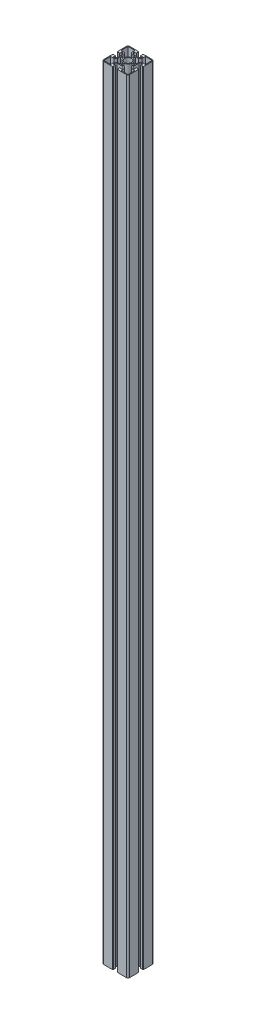
SolidWorks part; units mm, degrees
ref_plane "前视基准面" through (0, 0, 0) normal (0, 0, 1) x (1, 0, 0)
ref_plane "上视基准面" through (0, 0, 0) normal (0, 1, 0) x (1, 0, 0)
ref_plane "右视基准面" through (0, 0, 0) normal (1, 0, 0) x (0, 0, -1)
sketch "草图1" plane through (0, 0, 0) normal (0, 1, 0) x (1, 0, 0)
  line L0 (0, 32.6515) -> (0, -47.5) construction
  line L2 (-54.5455, 0) -> (57.7273, 0) construction
  line L82 (-16, 1) -> (-9.9499, 1)
  line L83 (-30, 6) -> (-28.5, 6)
  line L88 (-16, 1) -> (-16, 7.8284)
  line L89 (-16, 7.8284) -> (-20.1716, 12)
  line L90 (-20.1716, 12) -> (-28, 12)
  line L91 (-28, 12) -> (-28, 28)
  line L92 (-28, 28) -> (-12, 28)
  line L93 (-12, 28) -> (-12, 20.1716)
  line L94 (-12, 20.1716) -> (-7.8284, 16)
  line L95 (-7.8284, 16) -> (-1, 16)
  line L96 (-1, 16) -> (-1, 9.9499)
  line L97 (1, 9.9499) -> (1, 16)
  line L98 (1, 16) -> (7.8284, 16)
  line L99 (7.8284, 16) -> (12, 20.1716)
  line L100 (12, 20.1716) -> (12, 28)
  line L101 (12, 28) -> (28, 28)
  line L102 (28, 28) -> (28, 12)
  line L103 (28, 12) -> (20.1716, 12)
  line L104 (20.1716, 12) -> (16, 7.8284)
  line L105 (16, 7.8284) -> (16, 1)
  line L106 (16, 1) -> (9.9499, 1)
  line L107 (9.9499, -1) -> (16, -1)
  line L108 (16, -1) -> (16, -7.8284)
  line L109 (16, -7.8284) -> (20.1716, -12)
  line L110 (20.1716, -12) -> (28, -12)
  line L111 (28, -12) -> (28, -28)
  line L112 (28, -28) -> (12, -28)
  line L113 (12, -28) -> (12, -20.1716)
  line L114 (12, -20.1716) -> (7.8284, -16)
  line L115 (7.8284, -16) -> (1, -16)
  line L116 (1, -16) -> (1, -9.9499)
  line L117 (-1, -9.9499) -> (-1, -16)
  line L118 (-1, -16) -> (-7.8284, -16)
  line L119 (-7.8284, -16) -> (-12, -20.1716)
  line L120 (-12, -20.1716) -> (-12, -28)
  line L121 (-12, -28) -> (-28, -28)
  line L122 (-28, -28) -> (-28, -12)
  line L123 (-28, -12) -> (-20.1716, -12)
  line L124 (-20.1716, -12) -> (-16, -7.8284)
  line L125 (-16, -7.8284) -> (-16, -1)
  line L126 (-28.5, 6) -> (-28.5, 5)
  line L127 (-28.5, 5) -> (-24, 5)
  line L128 (-24, 5) -> (-24, 10)
  line L129 (-24, 10) -> (-21, 10)
  line L130 (-21, 10) -> (-18, 7)
  line L131 (-18, 7) -> (-18, -7)
  line L132 (-18, -7) -> (-21, -10)
  line L133 (-21, -10) -> (-24, -10)
  line L134 (-24, -10) -> (-24, -5)
  line L135 (-24, -5) -> (-28.5, -5)
  line L136 (-28.5, -5) -> (-28.5, -6)
  line L137 (-28.5, -6) -> (-30, -6)
  line L138 (-30, -6) -> (-30, -26)
  line L139 (-26, -30) -> (-6, -30)
  line L140 (-6, -30) -> (-6, -28.5)
  line L141 (-6, -28.5) -> (-5, -28.5)
  line L142 (-5, -28.5) -> (-5, -24)
  line L143 (-5, -24) -> (-10, -24)
  line L144 (-10, -24) -> (-10, -21)
  line L145 (-10, -21) -> (-7, -18)
  line L146 (-7, -18) -> (7, -18)
  line L147 (7, -18) -> (10, -21)
  line L148 (10, -21) -> (10, -24)
  line L149 (10, -24) -> (5, -24)
  line L150 (5, -24) -> (5, -28.5)
  line L151 (5, -28.5) -> (6, -28.5)
  line L152 (6, -28.5) -> (6, -30)
  line L153 (6, -30) -> (26, -30)
  line L154 (30, -26) -> (30, -6)
  line L155 (30, -6) -> (28.5, -6)
  line L156 (28.5, -6) -> (28.5, -5)
  line L157 (28.5, -5) -> (24, -5)
  line L158 (24, -5) -> (24, -10)
  line L159 (24, -10) -> (21, -10)
  line L160 (21, -10) -> (18, -7)
  line L161 (18, -7) -> (18, 7)
  line L162 (18, 7) -> (21, 10)
  line L163 (21, 10) -> (24, 10)
  line L164 (24, 10) -> (24, 5)
  line L165 (24, 5) -> (28.5, 5)
  line L166 (28.5, 5) -> (28.5, 6)
  line L167 (28.5, 6) -> (30, 6)
  line L168 (30, 6) -> (30, 26)
  line L169 (26, 30) -> (6, 30)
  line L170 (6, 30) -> (6, 28.5)
  line L171 (6, 28.5) -> (5, 28.5)
  line L172 (5, 28.5) -> (5, 24)
  line L173 (5, 24) -> (10, 24)
  line L174 (10, 24) -> (10, 21)
  line L175 (10, 21) -> (7, 18)
  line L176 (7, 18) -> (-7, 18)
  line L177 (-7, 18) -> (-10, 21)
  line L178 (-10, 21) -> (-10, 24)
  line L179 (-10, 24) -> (-5, 24)
  line L180 (-5, 24) -> (-5, 28.5)
  line L181 (-5, 28.5) -> (-6, 28.5)
  line L182 (-6, 28.5) -> (-6, 30)
  line L183 (-6, 30) -> (-26, 30)
  line L184 (-30, 26) -> (-30, 6)
  line L185 (-16, -1) -> (-9.9499, -1)
  arc A41 (-9.9499, -1) -> (-1, -9.9499) centre (0, 0) ccw
  circle A42 centre (0, 0) radius 8
  arc A43 (-26, -30) -> (-30, -26) centre (-26, -26) cw
  arc A44 (26, 30) -> (30, 26) centre (26, 26) cw
  arc A45 (-26, 30) -> (-30, 26) centre (-26, 26) ccw
  arc A46 (26, -30) -> (30, -26) centre (26, -26) ccw
  arc A47 (9.9499, 1) -> (1, 9.9499) centre (0, 0) ccw
  arc A48 (-1, 9.9499) -> (-9.9499, 1) centre (0, 0) ccw
  arc A49 (1, -9.9499) -> (9.9499, -1) centre (0, 0) ccw
  dimension "D1" = 60
extrude "凸台-拉伸1" add sketch "草图1" along normal blind 1800
ref_plane "基准面4" through (0, 1110, 0) normal (0, -1, 0) x (-1, 0, 0)
ref_plane "基准面5" through (0, 1350, 0) normal (0, -1, 0) x (-1, 0, 0)
ref_plane "基准面6" through (0, 1200, 0) normal (0, -1, 0) x (-1, 0, 0)
